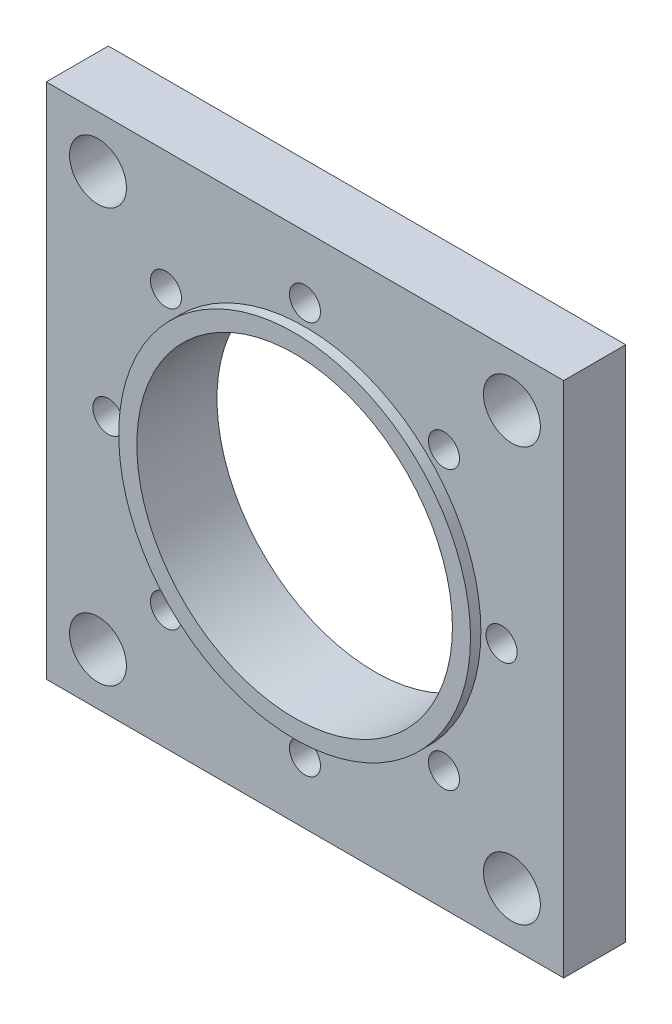
SolidWorks part; units mm, degrees
ref_plane "前视基准面" through (0, 0, 0) normal (0, 0, 1) x (1, 0, 0)
ref_plane "上视基准面" through (0, 0, 0) normal (0, 1, 0) x (1, 0, 0)
ref_plane "右视基准面" through (0, 0, 0) normal (1, 0, 0) x (0, 0, -1)
other "Configuration Table"
sketch "草图1" plane through (0, 0, 0) normal (0, 0, 1) x (1, 0, 0)
  line L1 (-50, 50) -> (50, 50)
  line L2 (-50, 50) -> (-50, -50)
  line L3 (-50, -50) -> (50, -50)
  line L4 (50, 50) -> (50, -50)
  line L5 (-50, 50) -> (50, -50) construction
  line L6 (-50, -50) -> (50, 50) construction
  point P0 (0, 0)
  dimension "D1" = 100
extrude "凸台-拉伸1" add sketch "草图1" along normal mid plane 15.5
sketch "草图2" plane through (0, 0, 7.75) normal (0, 0, 1) x (1, 0, 0)
  circle A0 centre (0, 0) radius 30.5
  dimension "D1" = 61
extrude "切除-拉伸1" cut sketch "草图2" against normal blind 17
sketch "草图3" plane through (0, 0, 7.75) normal (0, 0, 1) x (1, 0, 0)
  line L4 (50, -50) -> (50, 50)
  line L5 (50, 50) -> (-50, 50)
  line L6 (-50, 50) -> (-50, -50)
  line L7 (-50, -50) -> (50, -50)
  line L8 (50, -50) -> (50, 50)
  line L9 (50, 50) -> (-50, 50)
  line L10 (-50, 50) -> (-50, -50)
  line L11 (-50, -50) -> (50, -50)
  circle A2 centre (0, 0) radius 34
  circle A3 centre (0, 0) radius 34
  dimension "D1" = 0
  dimension "D2" = 3.5
extrude "切除-拉伸2" cut sketch "草图3" against normal blind 2
sketch "草图4" plane through (0, 0, -7.75) normal (0, 0, -1) x (-1, 0, 0)
  line L4 (-50, 50) -> (-50, -50)
  line L5 (-50, -50) -> (50, -50)
  line L6 (50, -50) -> (50, 50)
  line L7 (50, 50) -> (-50, 50)
  line L8 (-50, 50) -> (-50, -50)
  line L9 (-50, -50) -> (50, -50)
  line L10 (50, -50) -> (50, 50)
  line L11 (50, 50) -> (-50, 50)
  circle A0 centre (0, 0) radius 47.5
  dimension "D1" = 95
  dimension "D2" = 0
extrude "切除-拉伸3" cut sketch "草图4" against normal blind 1.5
sketch "草图5" plane through (0, 0, -7.75) normal (0, 0, -1) x (-1, 0, 0)
  circle A0 centre (0, 0) radius 38 construction
  dimension "D1" = 76
hole_wizard "M6 六角头螺栓的柱形沉头孔1" positions "草图6" profile "草图7" counterbore size "M6" standard "GB" end condition through all
sketch "草图6" plane through (0, 0, -7.75) normal (0, 0, -1) x (-1, 0, 0)
  circle A0 centre (0, 0) radius 38 construction
  point P0 (0, 38)
sketch "草图7" plane through (0, 38, -7.75) normal (1, 0, 0) x (0, 1, 0)
  line L0 (0, 0) -> (0, 15.5)
  line L1 (0, 15.5) -> (3, 15.5)
  line L3 (3, 15.5) -> (3, 6)
  line L4 (3, 6) -> (5, 6)
  line L5 (5, 6) -> (5, 0)
  line L7 (5, 0) -> (0, 0)
  line L11 (0, -6.35) -> (0, 107.95) construction
  dimension "通孔孔直径" = 6
  dimension "通孔孔深度" = 15.5
  dimension "柱形沉头孔直径" = 10
  dimension "柱形沉头孔深度" = 6
pattern_circular "阵列(圆周)1" count 8 over 360 about axis through (0, 0, 0) along (0, 0, 1) of "M6 六角头螺栓的柱形沉头孔1"
sketch "草图8" plane through (0, 0, -6.25) normal (0, 0, -1) x (-1, 0, 0)
  circle A0 centre (40, 40) radius 5.5
  circle A1 centre (40, -40) radius 5.5
  circle A2 centre (-40, -40) radius 5.5
  circle A3 centre (-40, 40) radius 5.5
  point P2 (-34.9424, 41.7422)
  point P3 (0, 0)
  point P12 (0, 0)
  dimension "D3" = 11
  dimension "D1" = 40
  dimension "D2" = 40
  dimension "D4" = 4
extrude "切除-拉伸4" cut sketch "草图8" against normal up to next
